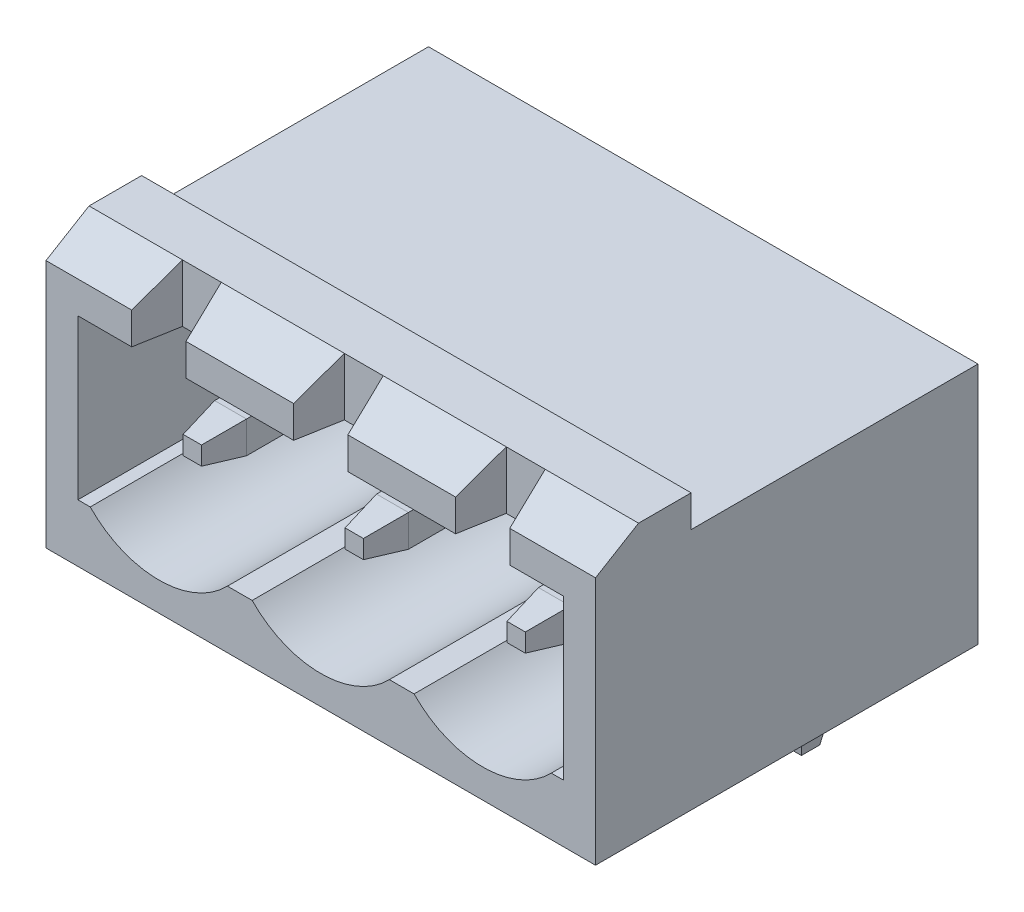
SolidWorks part; units mm, degrees
ref_plane "Front Plane" through (0, 0, 0) normal (0, 0, 1) x (1, 0, 0)
ref_plane "Top Plane" through (0, 0, 0) normal (0, 1, 0) x (1, 0, 0)
ref_plane "Right Plane" through (0, 0, 0) normal (1, 0, 0) x (0, 0, -1)
sketch "Sketch1" plane through (0, 0, 0) normal (0, 0, 1) x (1, 0, 0)
  line L1 (8.62, -3.81) -> (-8.62, -3.81)
  line L2 (8.62, -3.81) -> (8.62, 3.81)
  line L3 (8.62, 3.81) -> (-8.62, 3.81)
  line L4 (-8.62, -3.81) -> (-8.62, 3.81)
  line L5 (8.62, -3.81) -> (-8.62, 3.81) construction
  line L6 (8.62, 3.81) -> (-8.62, -3.81) construction
  point P0 (0, 0)
  dimension "D1" = 7.62
  dimension "D2" = 17.24
extrude "Boss-Extrude1" add sketch "Sketch1" along normal mid plane 12
sketch "Sketch7" plane through (8.62, 0, 0) normal (1, 0, 0) x (0, 0, -1)
  line L0 (-6, 3.81) -> (-6, 4)
  line L1 (-3, 4.81) -> (-6, 4.81) construction
  line L2 (-3, 4.81) -> (-3, 3.81) construction
  line L3 (-3, 3.81) -> (-6, 3.81) construction
  line L4 (-6, 4.81) -> (-6, 3.81) construction
  line L5 (-3, 4.81) -> (-6, 3.81) construction
  line L6 (-3, 3.81) -> (-6, 4.81) construction
  line L7 (-6, 4) -> (-4.65, 4.81)
  line L8 (-4.65, 4.81) -> (-3, 4.81)
  line L9 (-3, 4.81) -> (-3, 3.81)
  line L10 (-3, 3.81) -> (-6, 3.81)
  point P0 (-4.5, 4.31)
  point P6 (0, 0)
  dimension "D1" = 1
  dimension "D2" = 3
  dimension "D3" = 1.65
  dimension "D4" = 0.81
extrude "Boss-Extrude6" add sketch "Sketch7" against normal up to surface (17.24 mm away) up to face at (-8.62, 0, 0)
sketch "Sketch2" plane through (0, 0, 6) normal (0, 0, 1) x (1, 0, 0)
  line L0 (8.62, -3.81) -> (8.62, 4) construction
  line L1 (7.62, -2) -> (2.54, -2) construction
  line L2 (7.62, -2) -> (7.62, 3) construction
  line L3 (7.62, 3) -> (2.54, 3) construction
  line L4 (2.54, -2) -> (2.54, 3) construction
  line L5 (7.62, -2) -> (2.54, 3) construction
  line L6 (7.62, 3) -> (2.54, -2) construction
  line L7 (8.62, 3.81) -> (-8.62, 3.81) construction
  line L8 (-8.62, -3.81) -> (8.62, -3.81) construction
  line L9 (2.9278, -2) -> (2.54, -2)
  line L10 (2.54, -2) -> (2.54, 3)
  line L11 (2.54, 3) -> (7.62, 3)
  line L12 (7.62, 3) -> (7.62, -2)
  line L13 (7.62, -2) -> (7.2322, -2)
  arc A0 (2.9278, -2) -> (7.2322, -2) centre (5.08, 0.09) ccw
  point P0 (5.08, 0.5)
  point P15 (5.08, -2.91)
  dimension "D7" = 3
  dimension "D1" = 3.54
  dimension "D2" = 5.08
  dimension "D3" = 0.81
  dimension "D4" = 1.81
  dimension "D5" = 5
  dimension "D6" = 0.9
extrude "Cut-Extrude1" cut sketch "Sketch2" against normal blind 11.2
sketch "Sketch3" plane through (0, 0, -5.2) normal (0, 0, 1) x (1, 0, 0)
  line L0 (4.08, -1.028) -> (4.08, -2.7384)
  line L1 (6.08, -1.028) -> (6.08, -2.7384)
  line L2 (5.08, 0.09) -> (5.08, -0.91) construction
  line L3 (3.601, -0.16) -> (2.54, -0.16)
  line L4 (2.54, 3) -> (2.54, -2) construction
  line L5 (3.601, 0.34) -> (2.54, 0.34)
  line L6 (2.54, 0.34) -> (2.54, -0.16)
  line L7 (6.559, -0.16) -> (7.62, -0.16)
  line L8 (7.62, -2) -> (7.62, 3) construction
  line L9 (7.62, -0.16) -> (7.62, 0.34)
  line L10 (7.62, 0.34) -> (6.559, 0.34)
  line L11 (3.58, 0.09) -> (6.08, 0.09) construction
  line L12 (4.83, 1.569) -> (4.83, 3)
  line L13 (7.62, 3) -> (2.54, 3) construction
  line L14 (4.83, 3) -> (5.33, 3)
  line L15 (5.33, 3) -> (5.33, 1.569)
  line L16 (-8.62, -3.81) -> (8.62, -3.81) construction
  line L17 (5.08, -0.91) -> (5.08, -1.41) construction
  line L18 (5.08, -1.41) -> (5.08, -2.91) construction
  line L19 (6.08, 0.09) -> (6.58, 0.09) construction
  line L20 (6.58, 0.09) -> (7.62, 0.09) construction
  line L21 (2.54, 0.09) -> (3.58, 0.09) construction
  arc A0 (2.9278, -2) -> (7.2322, -2) centre (5.08, 0.09) ccw construction
  arc A1 (4.08, -2.7384) -> (6.08, -2.7384) centre (5.08, 0.09) ccw
  circle A2 centre (5.08, 0.09) radius 1 construction
  arc A3 (6.08, -1.028) -> (6.559, -0.16) centre (5.08, 0.09) ccw
  arc A4 (4.08, -1.028) -> (5.08, -1.41) centre (5.08, 0.09) ccw construction
  arc A5 (5.08, -1.41) -> (6.08, -1.028) centre (5.08, 0.09) ccw construction
  arc A6 (6.559, -0.16) -> (6.58, 0.09) centre (5.08, 0.09) ccw construction
  arc A7 (6.559, 0.34) -> (5.33, 1.569) centre (5.08, 0.09) ccw
  arc A8 (6.58, 0.09) -> (6.559, 0.34) centre (5.08, 0.09) ccw construction
  arc A9 (5.33, 1.569) -> (4.83, 1.569) centre (5.08, 0.09) ccw construction
  arc A10 (4.83, 1.569) -> (3.601, 0.34) centre (5.08, 0.09) ccw
  arc A11 (3.601, 0.34) -> (3.58, 0.09) centre (5.08, 0.09) ccw construction
  arc A12 (3.601, -0.16) -> (4.08, -1.028) centre (5.08, 0.09) ccw
  arc A13 (3.58, 0.09) -> (3.601, -0.16) centre (5.08, 0.09) ccw construction
  arc A14 (2.9278, -2) -> (4.08, -2.7384) centre (5.08, 0.09) ccw construction
  arc A15 (6.08, -2.7384) -> (7.2322, -2) centre (5.08, 0.09) ccw construction
  dimension "D1" = 2
  dimension "D2" = 3
  dimension "D3" = 2
  dimension "D4" = 0.5
  dimension "D5" = 0.5
  dimension "D6" = 3.9
  dimension "D7" = 3
extrude "Boss-Extrude2" add sketch "Sketch3" along normal blind 2.5
sketch "Sketch4" plane through (0, 0, -2.7) normal (0, 0, 1) x (1, 0, 0)
  circle A1 centre (5.08, 0.09) radius 1
  dimension "D1" = 2
extrude "Boss-Extrude3" add sketch "Sketch4" along normal offset from surface (0.7 mm away) 8 up to face at (5.08, -0.485, 6)
sketch "Sketch5" plane through (0, 0, -2) normal (0, 0, 1) x (1, 0, 0)
  line L1 (5.58, -0.41) -> (4.58, -0.41)
  line L2 (5.58, -0.41) -> (5.58, 0.59)
  line L3 (5.58, 0.59) -> (4.58, 0.59)
  line L4 (4.58, -0.41) -> (4.58, 0.59)
  line L5 (5.58, -0.41) -> (4.58, 0.59) construction
  line L6 (5.58, 0.59) -> (4.58, -0.41) construction
  point P0 (5.08, 0.09)
  dimension "D1" = 1
extrude "Boss-Extrude4" add sketch "Sketch5" along normal blind 5.75 separate body
sketch "Sketch6" plane through (0, 0, 3.75) normal (0, 0, 1) x (1, 0, 0)
  line L4 (4.58, 0.59) -> (4.58, -0.41)
  line L5 (4.58, -0.41) -> (5.58, -0.41)
  line L6 (5.58, -0.41) -> (5.58, 0.59)
  line L7 (5.58, 0.59) -> (4.58, 0.59)
  line L8 (4.58, 0.59) -> (4.58, -0.41)
  line L9 (4.58, -0.41) -> (5.58, -0.41)
  line L10 (5.58, -0.41) -> (5.58, 0.59)
  line L11 (5.58, 0.59) -> (4.58, 0.59)
  dimension "D1" = 0
extrude "Boss-Extrude5" add sketch "Sketch6" along normal blind 1.2 draft 10
sketch "Sketch9" plane through (0, 4.81, 0) normal (0, 1, 0) x (1, 0, 0)
  line L0 (5.08, 5.2) -> (5.08, -6) construction
  line L1 (7.62, -6) -> (2.54, -6) construction
  line L2 (4.23, -6) -> (4.47, -4.65)
  line L3 (-8.62, -4.65) -> (8.62, -4.65) construction
  line L4 (4.47, -4.65) -> (5.69, -4.65)
  line L5 (5.69, -4.65) -> (5.93, -6)
  line L6 (5.93, -6) -> (4.23, -6)
  point P2 (5.08, -4.65)
  dimension "D1" = 1.22
  dimension "D2" = 1.7
extrude "Cut-Extrude2" cut sketch "Sketch9" against normal up to next
sketch "Sketch10" plane through (0, -3.81, 0) normal (0, -1, 0) x (1, 0, 0)
  line L0 (5.08, -6) -> (5.08, 6) construction
  line L1 (-8.62, -6) -> (8.62, -6) construction
  line L2 (-8.62, 6) -> (8.62, 6) construction
  line L4 (4.58, -4.5) -> (5.58, -4.5)
  line L5 (4.58, -4.5) -> (4.58, -3.5)
  line L6 (4.58, -3.5) -> (5.58, -3.5)
  line L7 (5.58, -4.5) -> (5.58, -3.5)
  line L8 (4.58, -4.5) -> (5.58, -3.5) construction
  line L9 (4.58, -3.5) -> (5.58, -4.5) construction
  point P7 (5.08, -4)
  dimension "D1" = 10
  dimension "D2" = 1
extrude "Boss-Extrude7" add sketch "Sketch10" along normal blind 2.3 separate body
sketch "Sketch11" plane through (0, -6.11, 0) normal (0, -1, 0) x (1, 0, 0)
  line L4 (5.58, -4.5) -> (5.58, -3.5)
  line L5 (5.58, -3.5) -> (4.58, -3.5)
  line L6 (4.58, -3.5) -> (4.58, -4.5)
  line L7 (4.58, -4.5) -> (5.58, -4.5)
  line L8 (5.58, -4.5) -> (5.58, -3.5)
  line L9 (5.58, -3.5) -> (4.58, -3.5)
  line L10 (4.58, -3.5) -> (4.58, -4.5)
  line L11 (4.58, -4.5) -> (5.58, -4.5)
  dimension "D1" = 0
extrude "Boss-Extrude8" add sketch "Sketch11" along normal blind 1.2 draft 10
sketch "Sketch12" plane through (0, 0, -6) normal (0, 0, -1) x (-1, 0, 0)
  line L0 (-5.08, 0.09) -> (-5.08, -0.91) construction
  line L1 (-4.08, -3.81) -> (-6.08, -3.81)
  line L2 (-4.08, -3.81) -> (-4.08, 2.94)
  line L3 (-4.08, 2.94) -> (-6.08, 2.94)
  line L4 (-6.08, -3.81) -> (-6.08, 2.94)
  line L5 (-4.08, -3.81) -> (-6.08, 2.94) construction
  line L6 (-4.08, 2.94) -> (-6.08, -3.81) construction
  line L7 (8.62, -3.81) -> (-8.62, -3.81) construction
  point P0 (-5.08, -0.435)
  point P5 (0, 0)
  dimension "D1" = 6.75
  dimension "D2" = 2
extrude "Cut-Extrude3" cut sketch "Sketch12" against normal blind 0.5
pattern_linear "LPattern1" count 3 spacing 5.08 along (-1, 0, 0) of "Cut-Extrude1", "Boss-Extrude2", "Boss-Extrude3", "Cut-Extrude2", "Cut-Extrude3"
pattern_linear "LPattern2" count 3 spacing 5.08 along (-1, 0, 0) of bodies 111 106
equation "\"NumPins\"= 3'Number of pins on block"
equation "\"PinPitch\"= .2in'distance between pin centers"
equation "\"TerminalHeight\"= .3in'height of block"
equation "\"TerminalDepth\"= 12mm'depth of block"
equation "\"SideOffset\"= 1mm'offset on edges to provide space for side walls"
equation "\"PinSize\"= 1mm'side length of pin square profile"
equation "\"TerminalWidth\"= ( 2 * \"SideOffset\" ) + ( \"NumPins\" * \"PinPitch\" )"
equation "\"D2@Sketch1\"=\"NumPins\"*\"PinPitch\"+2*\"SideOffset\""
equation "\"D3@LPattern1\"=\"PinPitch\""
equation "\"D1@LPattern1\"=\"NumPins\""
equation "\"D2@Sketch10\"=\"PinSize\""
equation "\"D3@LPattern2\"=\"PinPitch\""
equation "\"D1@LPattern2\"=\"NumPins\""
